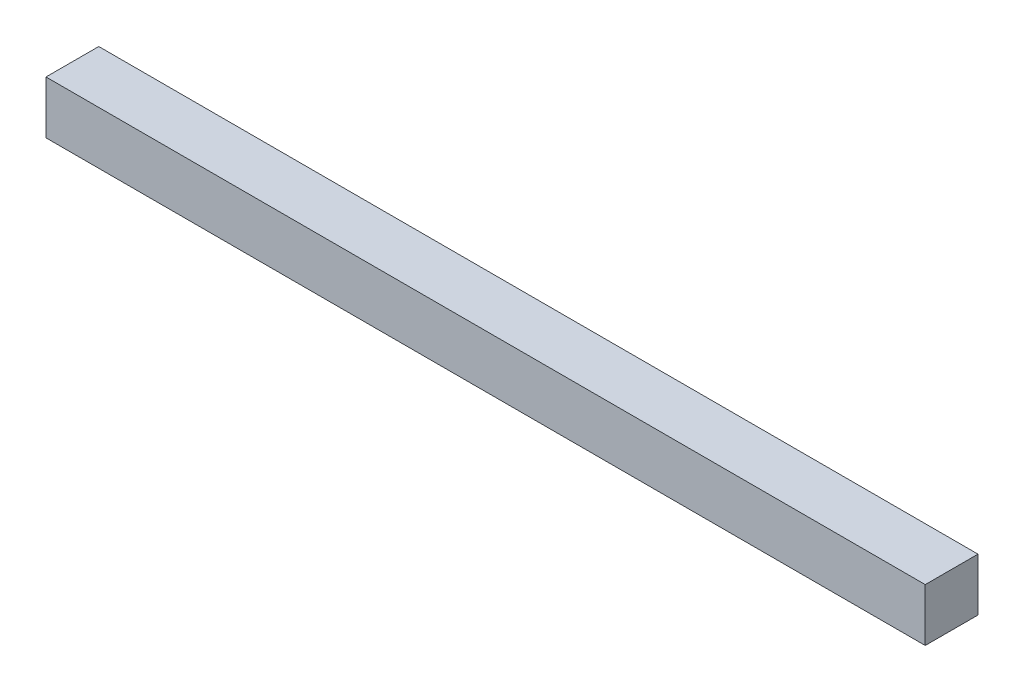
SolidWorks part; units mm, degrees
ref_plane "Front Plane" through (0, 0, 0) normal (0, 0, 1) x (1, 0, 0)
ref_plane "Top Plane" through (0, 0, 0) normal (0, 1, 0) x (1, 0, 0)
ref_plane "Right Plane" through (0, 0, 0) normal (1, 0, 0) x (0, 0, -1)
sketch "Sketch1" plane through (0, 0, 0) normal (1, 0, 0) x (0, 0, -1)
  line L1 (20.3959, 21.9635) -> (-9.6041, 21.9635)
  line L2 (20.3959, 21.9635) -> (20.3959, -8.0365)
  line L3 (20.3959, -8.0365) -> (-9.6041, -8.0365)
  line L4 (-9.6041, 21.9635) -> (-9.6041, -8.0365)
  dimension "D1" = 30
  dimension "D2" = 30
extrude "Boss-Extrude1" add sketch "Sketch1" along normal blind 500
